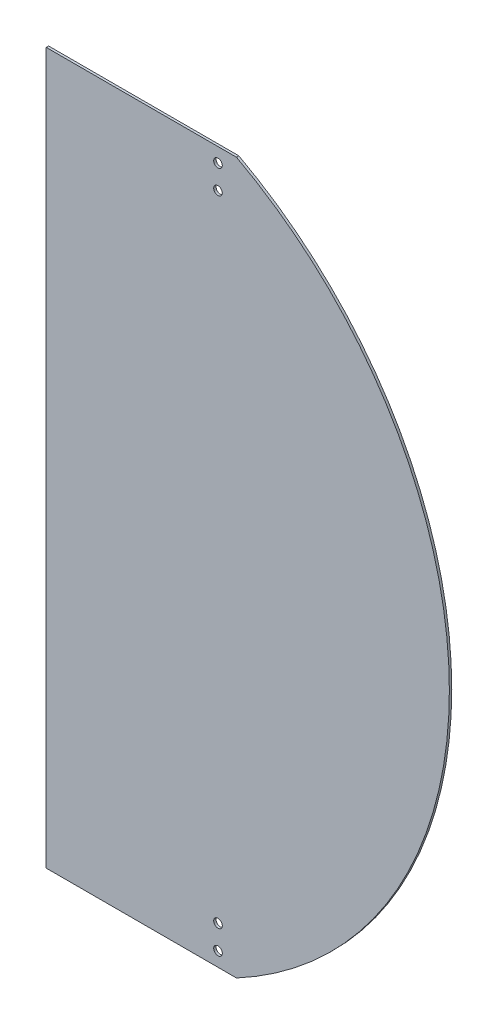
SolidWorks part; units mm, degrees
material "Galvanized Steel"
ref_plane "Front Plane" through (0, 0, 0) normal (0, 0, 1) x (1, 0, 0)
ref_plane "Top Plane" through (0, 0, 0) normal (0, 1, 0) x (1, 0, 0)
ref_plane "Right Plane" through (0, 0, 0) normal (1, 0, 0) x (0, 0, -1)
sketch "Sketch2" plane through (0, 0, 0) normal (0, 0, 1) x (1, 0, 0)
  line L0 (0, 372.5) -> (0, -372.5)
  line L2 (0, 372.5) -> (199.374, 372.5)
  line L3 (0, 0) -> (891.5875, 0) construction
  line L4 (0, -372.5) -> (199.374, -372.5)
  arc A1 (199.374, -372.5) -> (199.374, 372.5) centre (0, 0) ccw
extrude "Boss-Extrude1" add sketch "Sketch2" along normal blind 2.5
sketch "Sketch3" plane through (0, 0, 0) normal (0, 0, -1) x (-1, 0, 0)
  line L0 (-199.374, 372.5) -> (0, 372.5) construction
  line L1 (0, 372.5) -> (0, -372.5) construction
  circle A0 centre (-180, 357.5) radius 4.5
  circle A1 centre (-180, 332.5) radius 4.5
  dimension "D1" = 9
  dimension "D2" = 15
  dimension "D3" = 9
  dimension "D4" = 25
  dimension "D5" = 180
extrude "Cut-Extrude1" cut sketch "Sketch3" against normal through all both and the other way through all
ref_plane "Plane1" through (0, 0, 0) normal (0, 1, 0) x (1, 0, 0)
mirror "Mirror1" about plane through (0, 0, 0) normal (0, 1, 0) of "Cut-Extrude1"
